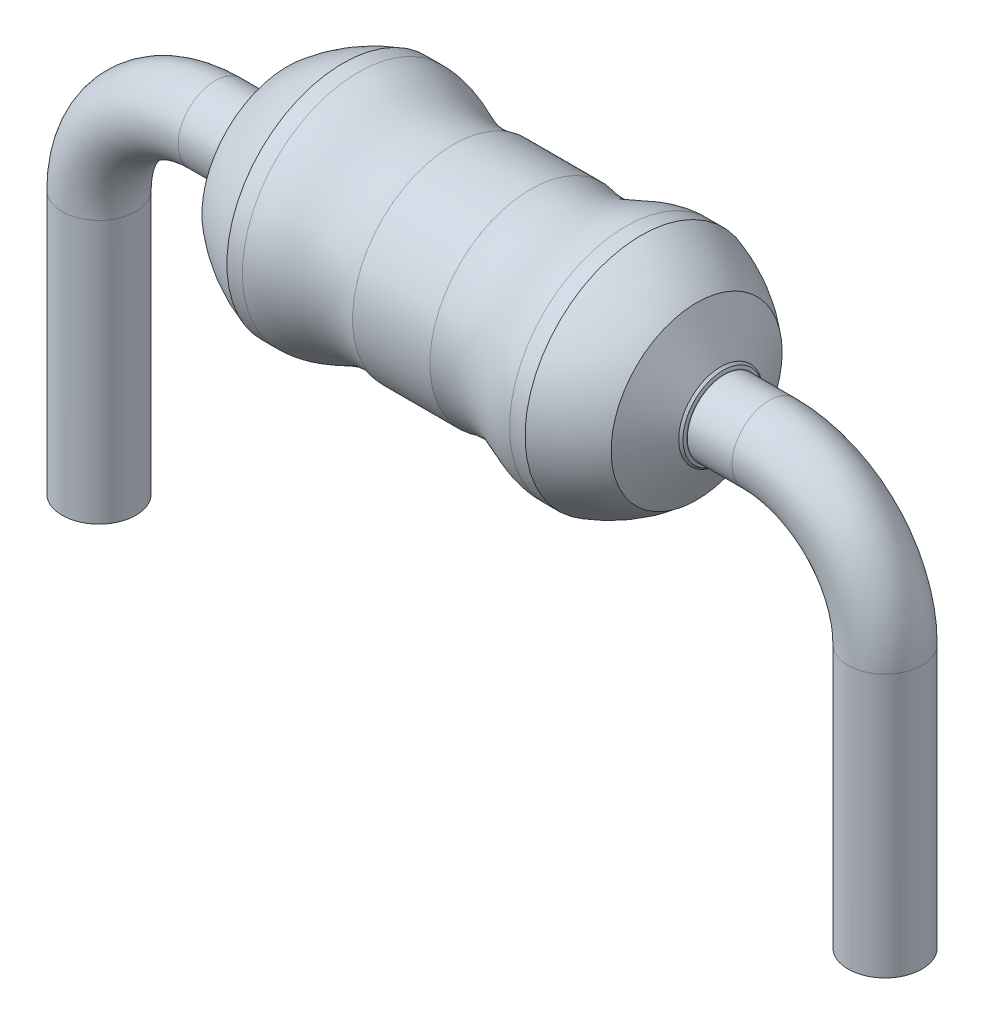
SolidWorks part; units mm, degrees
ref_plane "Спереди" through (0, 0, 0) normal (0, 0, 1) x (1, 0, 0)
ref_plane "Сверху" through (0, 0, 0) normal (0, 1, 0) x (1, 0, 0)
ref_plane "Справа" through (0, 0, 0) normal (1, 0, 0) x (0, 0, -1)
sketch "Croquis1" plane through (0, 0, 0) normal (0, 0, 1) x (1, 0, 0)
  line L0 (0, -0.6264) -> (0, 2.3312) construction
  line L1 (1.5, 0.2403) -> (1.5, 0)
  line L2 (1.5, 0.2403) -> (1.4925, 0.2586)
  line L3 (1.3223, 0.5527) -> (1.4775, 0.2711)
  line L7 (0.9634, 0.75) -> (0.8634, 0.75)
  line L8 (1.5, 0) -> (-1.5, 0)
  line L27 (26.5292, 0) -> (-26.8628, 0) construction
  line L38 (-0.25, 0.6515) -> (0.25, 0.6515)
  line L39 (-0.9634, 0.75) -> (-0.8634, 0.75)
  line L46 (-1.3223, 0.5527) -> (-1.4775, 0.2711)
  line L47 (-1.5, 0.2403) -> (-1.4925, 0.2586)
  line L48 (-1.5, 0.2403) -> (-1.5, 0)
  arc A0 (1.4925, 0.2586) -> (1.4775, 0.2711) centre (1.784, 0.6236) cw
  arc A1 (0.9634, 0.75) -> (1.3223, 0.5527) centre (0.6456, -0.2534) cw
  arc A11 (-0.9634, 0.75) -> (-1.3223, 0.5527) centre (-0.6456, -0.2534) ccw
  arc A12 (-1.4925, 0.2586) -> (-1.4775, 0.2711) centre (-1.784, 0.6236) ccw
  spline S0 degree 3 poles (0.8634, 0.75) (0.6298, 0.7535) (0.5406, 0.5769) (0.25, 0.6515) knots 0.141422 0.141422 0.141422 0.141422 1 1 1 1
  spline S5 degree 3 poles (-0.8634, 0.75) (-0.6298, 0.7535) (-0.5406, 0.5769) (-0.25, 0.6515) knots 0.141422 0.141422 0.141422 0.141422 1 1 1 1
  point P3 (-1.0436, 1.15)
  point P4 (-1.404, 0.3551)
  point P8 (0, 0)
  point P18 (-1.457, 0.2938)
  point P29 (0, 0.6515)
  point P30 (0, 0)
  point P31 (-1.4642, 0.2773)
  point P32 (-1.4955, 0.2562)
  point P33 (0, 0)
  point P34 (0, 0)
  point P35 (-1.4662, 0.2933)
  point P36 (-1.4898, 0.2653)
  point P37 (0, 0)
  point P38 (0, 0)
  point P39 (0, 0)
  point P40 (0, 0)
  point P41 (0, 0)
  point P42 (-1.3223, 0.5527)
  dimension "D1" = 0.1
  dimension "D2" = 0.25
  dimension "D3" = 0.75
  dimension "D4" = 1.5
revolve "Revolución1" add sketch "Croquis1" angle 360 about L27
fillet "Скругление2" radius 0.01 2 edges at (-1.5, 0, -0.2403) (1.5, 0, -0.2403)
sketch "Croquis5" plane through (1.5, 0, 0) normal (1, 0, 0) x (0, 0, -1)
  circle A1 centre (0, 0) radius 0.2384
  circle A2 centre (0, 0) radius 0.2384
  dimension "D1" = 0
sketch "Croquis6" plane through (0, 0, 0) normal (0, 0, 1) x (1, 0, 0)
  line L0 (1.5, 0) -> (1.79, 0)
  line L1 (1.5, -0.2384) -> (1.5, 0.2384) construction
  line L2 (2.54, -0.75) -> (2.54, -2.45)
  arc A0 (1.79, 0) -> (2.54, -0.75) centre (1.79, -0.75) cw
  dimension "D1" = 0.75
  dimension "D2" = 2.54
  dimension "D3" = 2.45
sweep "Barrer1" add profiles "Croquis5" path "Croquis6"
mirror "Simetría1" about plane through (0, 0, 0) normal (1, 0, 0) of "Barrer1"
